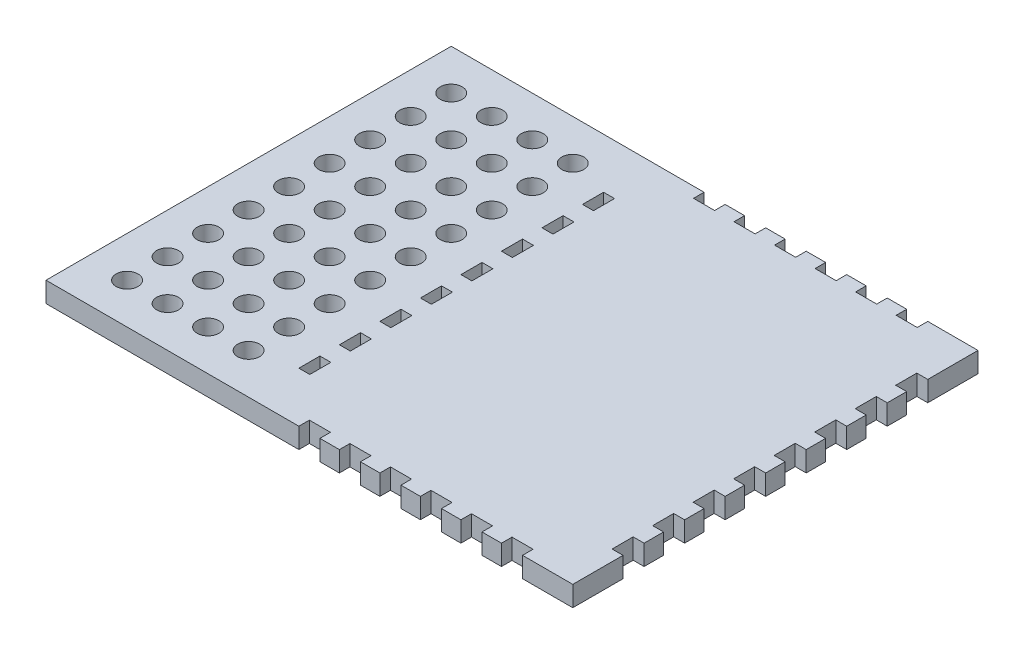
SolidWorks part; units mm, degrees
ref_plane "Front Plane" through (0, 0, 0) normal (0, 0, 1) x (1, 0, 0)
ref_plane "Top Plane" through (0, 0, 0) normal (0, 1, 0) x (1, 0, 0)
ref_plane "Right Plane" through (0, 0, 0) normal (1, 0, 0) x (0, 0, -1)
sketch "Sketch1" plane through (0, 0, 0) normal (0, 1, 0) x (1, 0, 0)
  line L1 (-50.8, -63.5) -> (50.8, -63.5)
  line L2 (-50.8, -63.5) -> (-50.8, 63.5)
  line L3 (-50.8, 63.5) -> (50.8, 63.5)
  line L4 (50.8, -63.5) -> (50.8, 63.5)
  line L5 (-50.8, -63.5) -> (50.8, 63.5) construction
  line L6 (-50.8, 63.5) -> (50.8, -63.5) construction
  line L11 (-41.275, -53.975) -> (41.275, 53.975) construction
  line L12 (-41.275, 53.975) -> (41.275, -53.975) construction
  point P0 (0, 0)
  point P5 (0, 0)
  dimension "D1" = 101.6
  dimension "D2" = 127
extrude "Boss-Extrude1" add sketch "Sketch1" along normal blind 6.35
sketch "Sketch2" plane through (0, 6.35, 0) normal (0, 1, 0) x (1, 0, 0)
  line L0 (-50.8, -63.5) -> (50.8, -63.5) construction
  line L1 (-35.052, -63.5) -> (-28.448, -63.5)
  line L2 (-35.052, -63.5) -> (-35.052, -60.198)
  line L3 (-35.052, -60.198) -> (-28.448, -60.198)
  line L4 (-28.448, -63.5) -> (-28.448, -60.198)
  line L5 (-22.352, -63.5) -> (-22.352, -60.198)
  line L6 (-22.352, -63.5) -> (-15.748, -63.5)
  line L7 (-15.748, -63.5) -> (-15.748, -60.198)
  line L8 (-22.352, -60.198) -> (-15.748, -60.198)
  line L9 (-9.652, -63.5) -> (-9.652, -60.198)
  line L10 (-9.652, -63.5) -> (-3.048, -63.5)
  line L11 (-3.048, -63.5) -> (-3.048, -60.198)
  line L12 (-9.652, -60.198) -> (-3.048, -60.198)
  line L13 (3.048, -63.5) -> (3.048, -60.198)
  line L14 (3.048, -63.5) -> (9.652, -63.5)
  line L15 (9.652, -63.5) -> (9.652, -60.198)
  line L16 (3.048, -60.198) -> (9.652, -60.198)
  line L17 (15.748, -63.5) -> (15.748, -60.198)
  line L18 (15.748, -63.5) -> (22.352, -63.5)
  line L19 (22.352, -63.5) -> (22.352, -60.198)
  line L20 (15.748, -60.198) -> (22.352, -60.198)
  line L21 (28.448, -63.5) -> (28.448, -60.198)
  line L22 (28.448, -63.5) -> (35.052, -63.5)
  line L23 (35.052, -63.5) -> (35.052, -60.198)
  line L24 (28.448, -60.198) -> (35.052, -60.198)
  line L25 (0, 0) -> (9.652, 0) construction
  line L26 (28.448, 60.198) -> (35.052, 60.198)
  line L27 (35.052, 63.5) -> (35.052, 60.198)
  line L28 (28.448, 63.5) -> (35.052, 63.5)
  line L29 (28.448, 63.5) -> (28.448, 60.198)
  line L30 (15.748, 60.198) -> (22.352, 60.198)
  line L31 (22.352, 63.5) -> (22.352, 60.198)
  line L32 (15.748, 63.5) -> (22.352, 63.5)
  line L33 (15.748, 63.5) -> (15.748, 60.198)
  line L34 (3.048, 60.198) -> (9.652, 60.198)
  line L35 (9.652, 63.5) -> (9.652, 60.198)
  line L36 (3.048, 63.5) -> (9.652, 63.5)
  line L37 (3.048, 63.5) -> (3.048, 60.198)
  line L38 (-9.652, 60.198) -> (-3.048, 60.198)
  line L39 (-3.048, 63.5) -> (-3.048, 60.198)
  line L40 (-9.652, 63.5) -> (-3.048, 63.5)
  line L41 (-9.652, 63.5) -> (-9.652, 60.198)
  line L42 (-22.352, 60.198) -> (-15.748, 60.198)
  line L43 (-15.748, 63.5) -> (-15.748, 60.198)
  line L44 (-22.352, 63.5) -> (-15.748, 63.5)
  line L45 (-22.352, 63.5) -> (-22.352, 60.198)
  line L46 (-28.448, 63.5) -> (-28.448, 60.198)
  line L47 (-35.052, 60.198) -> (-28.448, 60.198)
  line L48 (-35.052, 63.5) -> (-35.052, 60.198)
  line L49 (-35.052, 63.5) -> (-28.448, 63.5)
  line L50 (-50.8, 63.5) -> (-50.8, -63.5) construction
  line L51 (-50.8, 28.448) -> (-47.371, 28.448)
  line L52 (-50.8, 28.448) -> (-50.8, 35.052)
  line L53 (-50.8, 35.052) -> (-47.371, 35.052)
  line L54 (-47.371, 28.448) -> (-47.371, 35.052)
  line L55 (50.8, 63.5) -> (-50.8, 63.5) construction
  line L56 (-50.8, 15.748) -> (-47.371, 15.748)
  line L57 (-50.8, 15.748) -> (-50.8, 22.352)
  line L58 (-50.8, 22.352) -> (-47.371, 22.352)
  line L59 (-47.371, 15.748) -> (-47.371, 22.352)
  line L60 (-50.8, 3.048) -> (-47.371, 3.048)
  line L61 (-50.8, 3.048) -> (-50.8, 9.652)
  line L62 (-50.8, 9.652) -> (-47.371, 9.652)
  line L63 (-47.371, 3.048) -> (-47.371, 9.652)
  line L64 (-50.8, -9.652) -> (-47.371, -9.652)
  line L65 (-50.8, -9.652) -> (-50.8, -3.048)
  line L66 (-50.8, -3.048) -> (-47.371, -3.048)
  line L67 (-47.371, -9.652) -> (-47.371, -3.048)
  line L68 (-50.8, -22.352) -> (-47.371, -22.352)
  line L69 (-50.8, -22.352) -> (-50.8, -15.748)
  line L70 (-50.8, -15.748) -> (-47.371, -15.748)
  line L71 (-47.371, -22.352) -> (-47.371, -15.748)
  line L72 (-50.8, -35.052) -> (-47.371, -35.052)
  line L73 (-50.8, -35.052) -> (-50.8, -28.448)
  line L74 (-50.8, -28.448) -> (-47.371, -28.448)
  line L75 (-47.371, -35.052) -> (-47.371, -28.448)
  line L84 (0, 0) -> (0, 15.748) construction
  line L93 (47.371, -35.052) -> (47.371, -28.448)
  line L94 (50.8, -28.448) -> (47.371, -28.448)
  line L95 (50.8, -35.052) -> (50.8, -28.448)
  line L96 (50.8, -35.052) -> (47.371, -35.052)
  line L97 (47.371, -22.352) -> (47.371, -15.748)
  line L98 (50.8, -15.748) -> (47.371, -15.748)
  line L99 (50.8, -22.352) -> (50.8, -15.748)
  line L100 (50.8, -22.352) -> (47.371, -22.352)
  line L101 (47.371, -9.652) -> (47.371, -3.048)
  line L102 (50.8, -3.048) -> (47.371, -3.048)
  line L103 (50.8, -9.652) -> (50.8, -3.048)
  line L104 (50.8, -9.652) -> (47.371, -9.652)
  line L105 (47.371, 3.048) -> (47.371, 9.652)
  line L106 (50.8, 9.652) -> (47.371, 9.652)
  line L107 (50.8, 3.048) -> (50.8, 9.652)
  line L108 (50.8, 3.048) -> (47.371, 3.048)
  line L109 (47.371, 15.748) -> (47.371, 22.352)
  line L110 (50.8, 22.352) -> (47.371, 22.352)
  line L111 (50.8, 15.748) -> (50.8, 22.352)
  line L112 (50.8, 15.748) -> (47.371, 15.748)
  line L113 (47.371, 28.448) -> (47.371, 35.052)
  line L114 (50.8, 35.052) -> (47.371, 35.052)
  line L115 (50.8, 28.448) -> (50.8, 35.052)
  line L116 (50.8, 28.448) -> (47.371, 28.448)
  line L117 (-50.8, -47.752) -> (-47.371, -47.752) [skipped]
  line L118 (-50.8, -47.752) -> (-50.8, -41.148) [skipped]
  line L119 (-50.8, -41.148) -> (-47.371, -41.148) [skipped]
  line L120 (-47.371, -47.752) -> (-47.371, -41.148) [skipped]
  line L121 (-50.8, -60.452) -> (-47.371, -60.452) [skipped]
  line L122 (-50.8, -60.452) -> (-50.8, -53.848) [skipped]
  line L123 (-50.8, -53.848) -> (-47.371, -53.848) [skipped]
  line L124 (-47.371, -60.452) -> (-47.371, -53.848) [skipped]
  line L125 (-50.8, 41.148) -> (-47.371, 41.148)
  line L126 (-50.8, 41.148) -> (-50.8, 47.752)
  line L127 (-50.8, 47.752) -> (-47.371, 47.752)
  line L128 (-47.371, 41.148) -> (-47.371, 47.752)
  line L129 (-50.8, -47.752) -> (-47.371, -47.752)
  line L130 (-50.8, -47.752) -> (-50.8, -41.148)
  line L131 (-50.8, -41.148) -> (-47.371, -41.148)
  line L132 (-47.371, -47.752) -> (-47.371, -41.148)
  line L133 (47.371, -47.752) -> (47.371, -41.148)
  line L134 (50.8, -41.148) -> (47.371, -41.148)
  line L135 (50.8, -47.752) -> (50.8, -41.148)
  line L136 (50.8, -47.752) -> (47.371, -47.752)
  line L137 (47.371, 41.148) -> (47.371, 47.752)
  line L138 (50.8, 47.752) -> (47.371, 47.752)
  line L139 (50.8, 41.148) -> (50.8, 47.752)
  line L140 (50.8, 41.148) -> (47.371, 41.148)
  point P6 (-31.75, -63.5)
  point P65 (-50.8, 31.75)
  dimension "D1" = 6.604
  dimension "D2" = 3.302
  dimension "D3" = 19.05
  dimension "D5" = 2
  dimension "D6" = 31.75
  dimension "D8" = 12.7
  dimension "D9" = 2
  dimension "D10" = 6.604
  dimension "D4" = 6
  dimension "D7" = 8
  dimension "D11" = 2
  dimension "D12" = 2
extrude "Cut-Extrude1" cut sketch "Sketch2" against normal through all
sketch "Sketch3" plane through (0, 6.35, 0) normal (0, 1, 0) x (1, 0, 0)
  line L1 (-50.8, 63.5) -> (-114.3, 63.5)
  line L2 (-50.8, 63.5) -> (-50.8, -63.5)
  line L3 (-50.8, -63.5) -> (-114.3, -63.5)
  line L4 (-114.3, 63.5) -> (-114.3, -63.5)
  line L5 (-50.8, -63.5) -> (-35.052, -63.5) construction
  circle A0 centre (-101.6, 50.8) radius 3.429
  circle A1 centre (-88.9, 50.8) radius 3.429
  circle A2 centre (-88.9, 38.1) radius 3.429
  circle A6 centre (-101.6, 38.1) radius 3.429
  circle A10 centre (-101.6, 25.4) radius 3.429
  circle A11 centre (-88.9, 25.4) radius 3.429
  circle A12 centre (-76.2, 50.8) radius 3.429
  circle A13 centre (-63.5, 50.8) radius 3.429
  circle A14 centre (-76.2, 38.1) radius 3.429
  circle A15 centre (-63.5, 38.1) radius 3.429
  circle A16 centre (-76.2, 25.4) radius 3.429
  circle A17 centre (-63.5, 25.4) radius 3.429
  circle A18 centre (-101.6, 12.7) radius 3.429
  circle A19 centre (-88.9, 12.7) radius 3.429
  circle A20 centre (-76.2, 12.7) radius 3.429
  circle A21 centre (-63.5, 12.7) radius 3.429
  circle A22 centre (-101.6, 0) radius 3.429
  circle A23 centre (-88.9, 0) radius 3.429
  circle A24 centre (-76.2, 0) radius 3.429
  circle A25 centre (-63.5, 0) radius 3.429
  circle A26 centre (-101.6, -12.7) radius 3.429
  circle A27 centre (-88.9, -12.7) radius 3.429
  circle A28 centre (-76.2, -12.7) radius 3.429
  circle A29 centre (-63.5, -12.7) radius 3.429
  circle A30 centre (-101.6, -25.4) radius 3.429
  circle A31 centre (-88.9, -25.4) radius 3.429
  circle A32 centre (-76.2, -25.4) radius 3.429
  circle A33 centre (-63.5, -25.4) radius 3.429
  circle A34 centre (-101.6, -38.1) radius 3.429
  circle A35 centre (-88.9, -38.1) radius 3.429
  circle A36 centre (-76.2, -38.1) radius 3.429
  circle A37 centre (-63.5, -38.1) radius 3.429
  circle A38 centre (-101.6, -50.8) radius 3.429
  circle A39 centre (-88.9, -50.8) radius 3.429
  circle A40 centre (-76.2, -50.8) radius 3.429
  circle A41 centre (-63.5, -50.8) radius 3.429
  dimension "D2" = 6.858
  dimension "D4" = 12.7
  dimension "D1" = 63.5
  dimension "D3" = 38.1
  dimension "D7" = 12.7
  dimension "D8" = 12.7
  dimension "D5" = 4
  dimension "D6" = 9
extrude "Boss-Extrude2" add sketch "Sketch3" against normal blind 6.35
